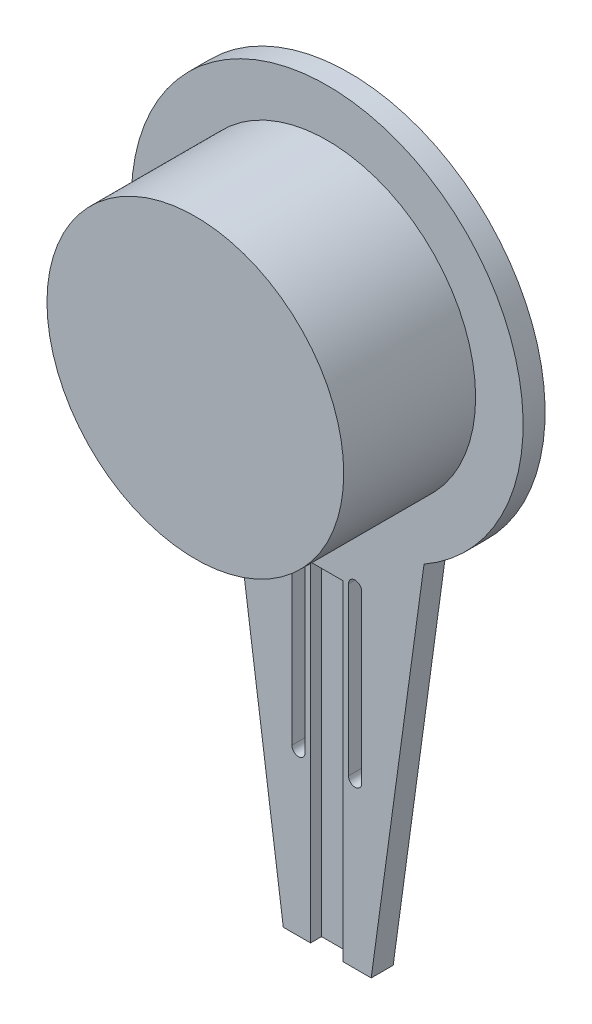
SolidWorks part; units mm, degrees
ref_plane "Front Plane" through (0, 0, 0) normal (0, 0, 1) x (1, 0, 0)
ref_plane "Top Plane" through (0, 0, 0) normal (0, 1, 0) x (1, 0, 0)
ref_plane "Right Plane" through (0, 0, 0) normal (1, 0, 0) x (0, 0, -1)
sketch "Sketch1" plane through (0, 0, 0) normal (0, 0, 1) x (1, 0, 0)
  line L15 (-26.0552, -104.4556) -> (-36.2152, -104.4556)
  line L16 (-36.2152, -104.4556) -> (-41.2952, -104.4556)
  line L17 (-26.0552, -104.4556) -> (-20.9752, -104.4556)
  line L18 (-53.5041, -15.5118) -> (-41.2952, -104.4556)
  line L19 (-8.7662, -15.5118) -> (-20.9752, -104.4556)
  arc A0 (-8.7662, -15.5118) -> (-53.5041, -15.5118) centre (-31.1352, 23.8451) ccw
  dimension "D1" = 88.9438
  dimension "D5" = 45.2695
  dimension "D2" = 88.9438
  dimension "D3" = 5.08
  dimension "D4" = 5.08
  dimension "D6" = 10.16
extrude "Boss-Extrude1" add sketch "Sketch1" along normal blind 5.08 contours A0 L18 L16 L15 L17 L19
sketch "Sketch3" plane through (0, 0, 5.08) normal (0, 0, 1) x (1, 0, 0)
sketch "Sketch4" plane through (0, 0, 5.08) normal (0, 0, 1) x (1, 0, 0)
  line L1 (-41.2952, -104.4556) -> (-20.9752, -104.4556) construction
  line L2 (-34.9927, -104.4556) -> (-34.9927, -28.2048)
  line L4 (-27.4955, -104.4556) -> (-27.4955, -28.2048)
  line L5 (-27.4955, -28.2048) -> (-34.9927, -28.2048)
  line L6 (-34.9927, -104.4556) -> (-27.4955, -104.4556)
extrude "Cut-Extrude3" cut sketch "Sketch4" against normal blind 2.54 contours L6 L2 L5 L4
sketch "Sketch5" plane through (0, 0, 5.08) normal (0, 0, 1) x (1, 0, 0)
  line L0 (-34.9927, -28.2048) -> (-51.7618, -28.2048)
  line L1 (-53.5041, -15.5118) -> (-41.2952, -104.4556) construction
  line L2 (-27.4955, -28.2048) -> (-10.5085, -28.2048)
  line L3 (-8.7662, -15.5118) -> (-20.9752, -104.4556) construction
  line L4 (-34.9927, -28.2048) -> (-37.7867, -28.2048)
  line L5 (-37.7867, -28.2048) -> (-37.7867, -67.0406) construction
  line L6 (-36.2627, -28.2048) -> (-36.2627, -67.0406)
  line L7 (-39.3107, -28.2048) -> (-39.3107, -67.0406)
  line L8 (-27.4955, -28.2048) -> (-24.7015, -28.2048)
  line L9 (-24.7015, -28.2048) -> (-24.7015, -66.617) construction
  line L10 (-23.1775, -28.2048) -> (-23.1775, -66.617)
  line L11 (-26.2255, -28.2048) -> (-26.2255, -66.617)
  arc A0 (-36.2627, -28.2048) -> (-39.3107, -28.2048) centre (-37.7867, -28.2048) ccw
  arc A1 (-39.3107, -67.0406) -> (-36.2627, -67.0406) centre (-37.7867, -67.0406) ccw
  arc A2 (-23.1775, -28.2048) -> (-26.2255, -28.2048) centre (-24.7015, -28.2048) ccw
  arc A3 (-26.2255, -66.617) -> (-23.1775, -66.617) centre (-24.7015, -66.617) ccw
  point P10 (-37.7867, -47.6227)
  point P17 (-24.7015, -47.4109)
  dimension "D1" = 1.524
  dimension "D2" = 1.524
  dimension "D3" = 1.27
  dimension "D4" = 1.27
extrude "Cut-Extrude4" cut sketch "Sketch5" against normal blind 5.08 contours L6 A1 L7 A0 | L10 A3 L11 A2
sketch3d "3DSketch2"
  circle A0 centre (-106.7474, 0, 29.3597) radius 10.16
  point P2 (-106.7474, 10.16, 29.3597)
  dimension "D1" = 20.32
sketch "Sketch8" plane through (0, 0, 5.08) normal (0, 0, 1) x (1, 0, 0)
sketch "Sketch9" plane through (0, 0, 5.08) normal (0, 0, 1) x (1, 0, 0)
sketch "Sketch11" plane through (0, 0, 5.08) normal (0, 0, 1) x (1, 0, 0)
  circle A0 centre (-31.1352, 23.8451) radius 34.29
extrude "Boss-Extrude3" add sketch "Sketch11" along normal blind 30.48
